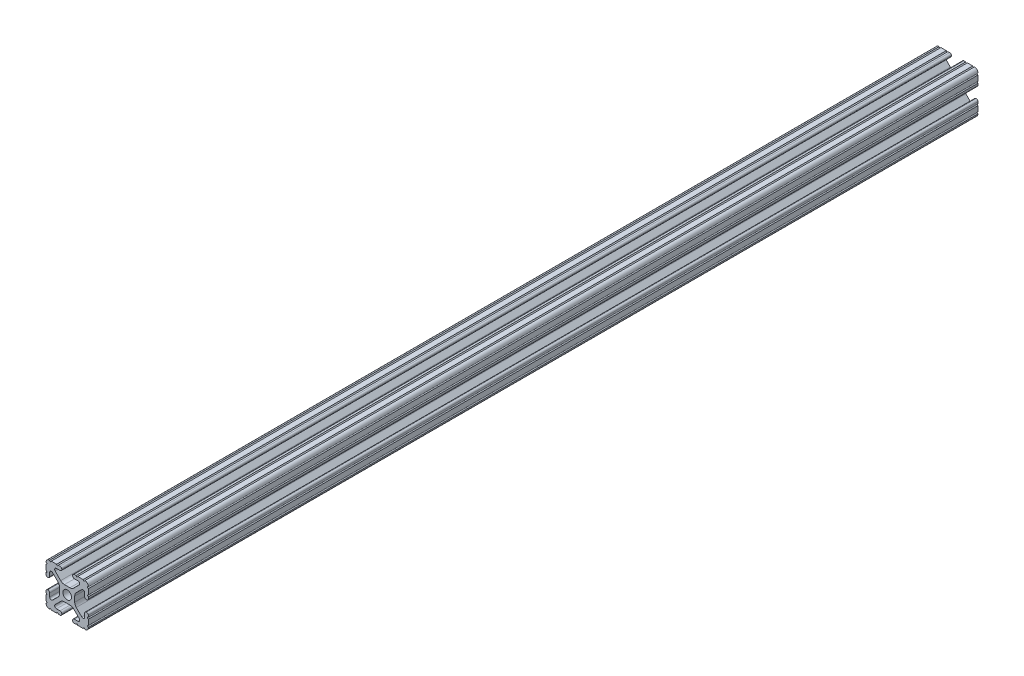
SolidWorks part; units mm, degrees
ref_plane "Front Plane" through (0, 0, 0) normal (0, 0, 1) x (1, 0, 0)
ref_plane "Top Plane" through (0, 0, 0) normal (0, 1, 0) x (1, 0, 0)
ref_plane "Right Plane" through (0, 0, 0) normal (1, 0, 0) x (0, 0, -1)
sketch "Sketch1" plane through (0, 0, 0) normal (0, 0, 1) x (1, 0, 0)
  line L0 (-7.207, 8.7244) -> (-3.8983, 5.4232)
  line L1 (-4.2875, 10.4902) -> (-6.4768, 10.4902)
  line L2 (-3.2385, 11.651) -> (-3.2385, 11.5392)
  line L3 (-5.3171, 12.7) -> (-4.2875, 12.7)
  line L4 (0, 13.4005) -> (0, -14.8534) construction
  line L5 (12.7, 0) -> (-13.9989, 0) construction
  line L6 (-9.5504, 12.7) -> (-6.3331, 12.7)
  line L7 (-12.7, 6.3331) -> (-12.7, 9.5504)
  line L8 (-12.7, 4.2875) -> (-12.7, 5.3171)
  line L9 (-11.5392, 3.2385) -> (-11.651, 3.2385)
  line L10 (-10.4902, 6.4021) -> (-10.4902, 4.2875)
  line L11 (-5.441, 3.8408) -> (-8.7371, 7.1294)
  line L12 (-4.5085, -1.5932) -> (-4.5085, 1.5932)
  line L13 (-1.7093, -4.4958) -> (1.7093, -4.4958)
  line L14 (3.9523, -5.4237) -> (7.1797, -8.6452)
  line L15 (6.4164, -10.4902) -> (4.2875, -10.4902)
  line L16 (3.2385, -11.5392) -> (3.2385, -11.651)
  line L17 (4.2875, -12.7) -> (5.3171, -12.7)
  line L18 (6.3331, -12.7) -> (9.5504, -12.7)
  line L19 (12.7, -9.5504) -> (12.7, -6.3331)
  line L20 (12.7, -5.3171) -> (12.7, -4.2875)
  line L21 (11.651, -3.2385) -> (11.5392, -3.2385)
  line L22 (10.4902, -4.2875) -> (10.4902, -6.4021)
  line L23 (8.7371, -7.1294) -> (5.441, -3.8408)
  line L24 (4.5085, -1.5932) -> (4.5085, 1.5932)
  line L25 (5.441, 3.8408) -> (8.7371, 7.1294)
  line L26 (10.4902, 6.4021) -> (10.4902, 4.2875)
  line L27 (11.5392, 3.2385) -> (11.651, 3.2385)
  line L28 (12.7, 4.2875) -> (12.7, 5.3171)
  line L29 (12.7, 6.3331) -> (12.7, 9.5504)
  line L30 (9.5504, 12.7) -> (6.3331, 12.7)
  line L31 (5.3171, 12.7) -> (4.2875, 12.7)
  line L32 (3.2385, 11.651) -> (3.2385, 11.5392)
  line L33 (4.2875, 10.4902) -> (6.4768, 10.4902)
  line L34 (7.207, 8.7244) -> (3.8983, 5.4232)
  line L35 (1.6558, 4.4958) -> (-1.6558, 4.4958)
  line L36 (-8.7371, -7.1294) -> (-5.441, -3.8408)
  line L37 (-10.4902, -4.2875) -> (-10.4902, -6.4021)
  line L38 (-11.651, -3.2385) -> (-11.5392, -3.2385)
  line L39 (-12.7, -5.3171) -> (-12.7, -4.2875)
  line L40 (-12.7, -9.5504) -> (-12.7, -6.3331)
  line L41 (-6.3331, -12.7) -> (-9.5504, -12.7)
  line L42 (-4.2875, -12.7) -> (-5.3171, -12.7)
  line L43 (-3.2385, -11.5392) -> (-3.2385, -11.651)
  line L44 (-6.4164, -10.4902) -> (-4.2875, -10.4902)
  line L45 (-3.9523, -5.4237) -> (-7.1797, -8.6452)
  arc A0 (-7.207, 8.7244) -> (-6.4768, 10.4902) centre (-6.4768, 9.4563) cw
  arc A1 (-3.2385, 11.5392) -> (-4.2875, 10.4902) centre (-4.2875, 11.5392) cw
  arc A2 (-4.2875, 12.7) -> (-3.2385, 11.651) centre (-4.2875, 11.651) cw
  arc A3 (-5.3171, 12.7) -> (-6.3331, 12.7) centre (-5.8251, 12.7) cw
  arc A4 (-9.5504, 12.7) -> (-10.5664, 12.6998) centre (-10.0584, 12.7) cw
  arc A5 (-12.6998, 10.5664) -> (-10.5664, 12.6998) centre (-10.5918, 10.5918) cw
  arc A6 (-12.6998, 10.5664) -> (-12.7, 9.5504) centre (-12.7, 10.0584) cw
  arc A7 (-12.7, 6.3331) -> (-12.7, 5.3171) centre (-12.7, 5.8251) cw
  arc A8 (-11.651, 3.2385) -> (-12.7, 4.2875) centre (-11.651, 4.2875) cw
  arc A9 (-10.4902, 4.2875) -> (-11.5392, 3.2385) centre (-11.5392, 4.2875) cw
  circle A10 centre (0, 0) radius 2.6035
  arc A11 (-10.4902, 6.4021) -> (-8.7371, 7.1294) centre (-9.4628, 6.4021) cw
  arc A12 (-5.441, 3.8408) -> (-4.5085, 1.5932) centre (-7.6835, 1.5932) cw
  arc A13 (-4.5085, -1.5932) -> (-5.441, -3.8408) centre (-7.6835, -1.5932) cw
  arc A14 (-8.7371, -7.1294) -> (-10.4902, -6.4021) centre (-9.4628, -6.4021) cw
  arc A15 (-1.7093, -4.4958) -> (-3.9523, -5.4237) centre (-1.7093, -7.6708) ccw
  arc A16 (3.9523, -5.4237) -> (1.7093, -4.4958) centre (1.7093, -7.6708) ccw
  arc A17 (6.4164, -10.4902) -> (7.1797, -8.6452) centre (6.4164, -9.4098) ccw
  arc A18 (4.2875, -10.4902) -> (3.2385, -11.5392) centre (4.2875, -11.5392) ccw
  arc A19 (3.2385, -11.651) -> (4.2875, -12.7) centre (4.2875, -11.651) ccw
  arc A20 (6.3331, -12.7) -> (5.3171, -12.7) centre (5.8251, -12.7) ccw
  arc A21 (10.5664, -12.6998) -> (9.5504, -12.7) centre (10.0584, -12.7) ccw
  arc A22 (10.5664, -12.6998) -> (12.6998, -10.5664) centre (10.5918, -10.5918) ccw
  arc A23 (12.7, -9.5504) -> (12.6998, -10.5664) centre (12.7, -10.0584) ccw
  arc A24 (12.7, -5.3171) -> (12.7, -6.3331) centre (12.7, -5.8251) ccw
  arc A25 (12.7, -4.2875) -> (11.651, -3.2385) centre (11.651, -4.2875) ccw
  arc A26 (11.5392, -3.2385) -> (10.4902, -4.2875) centre (11.5392, -4.2875) ccw
  arc A27 (8.7371, -7.1294) -> (10.4902, -6.4021) centre (9.4628, -6.4021) ccw
  arc A28 (4.5085, -1.5932) -> (5.441, -3.8408) centre (7.6835, -1.5932) ccw
  arc A29 (5.441, 3.8408) -> (4.5085, 1.5932) centre (7.6835, 1.5932) ccw
  arc A30 (10.4902, 6.4021) -> (8.7371, 7.1294) centre (9.4628, 6.4021) ccw
  arc A31 (10.4902, 4.2875) -> (11.5392, 3.2385) centre (11.5392, 4.2875) ccw
  arc A32 (11.651, 3.2385) -> (12.7, 4.2875) centre (11.651, 4.2875) ccw
  arc A33 (12.7, 6.3331) -> (12.7, 5.3171) centre (12.7, 5.8251) ccw
  arc A34 (12.6998, 10.5664) -> (12.7, 9.5504) centre (12.7, 10.0584) ccw
  arc A35 (12.6998, 10.5664) -> (10.5664, 12.6998) centre (10.5918, 10.5918) ccw
  arc A36 (9.5504, 12.7) -> (10.5664, 12.6998) centre (10.0584, 12.7) ccw
  arc A37 (5.3171, 12.7) -> (6.3331, 12.7) centre (5.8251, 12.7) ccw
  arc A38 (4.2875, 12.7) -> (3.2385, 11.651) centre (4.2875, 11.651) ccw
  arc A39 (3.2385, 11.5392) -> (4.2875, 10.4902) centre (4.2875, 11.5392) ccw
  arc A40 (7.207, 8.7244) -> (6.4768, 10.4902) centre (6.4768, 9.4563) ccw
  arc A41 (1.6558, 4.4958) -> (3.8983, 5.4232) centre (1.6558, 7.6708) ccw
  arc A42 (-1.6558, 4.4958) -> (-3.8983, 5.4232) centre (-1.6558, 7.6708) cw
  arc A43 (-11.5392, -3.2385) -> (-10.4902, -4.2875) centre (-11.5392, -4.2875) cw
  arc A44 (-12.7, -4.2875) -> (-11.651, -3.2385) centre (-11.651, -4.2875) cw
  arc A45 (-12.7, -5.3171) -> (-12.7, -6.3331) centre (-12.7, -5.8251) cw
  arc A46 (-12.7, -9.5504) -> (-12.6998, -10.5664) centre (-12.7, -10.0584) cw
  arc A47 (-10.5664, -12.6998) -> (-12.6998, -10.5664) centre (-10.5918, -10.5918) cw
  arc A48 (-10.5664, -12.6998) -> (-9.5504, -12.7) centre (-10.0584, -12.7) cw
  arc A49 (-6.3331, -12.7) -> (-5.3171, -12.7) centre (-5.8251, -12.7) cw
  arc A50 (-3.2385, -11.651) -> (-4.2875, -12.7) centre (-4.2875, -11.651) cw
  arc A51 (-4.2875, -10.4902) -> (-3.2385, -11.5392) centre (-4.2875, -11.5392) cw
  arc A52 (-6.4164, -10.4902) -> (-7.1797, -8.6452) centre (-6.4164, -9.4098) cw
  dimension "D1" = 5.207
  dimension "D9" = 14.859
  dimension "D2" = 25.4
  dimension "D3" = 12.7
  dimension "D4" = 6.477
  dimension "D5" = 8.2042
  dimension "D6" = 9.017
  dimension "D8" = 2.2098
  dimension "D10" = 2.2098
extrude "Extrude1" add sketch "Sketch1" against normal blind 533.4
